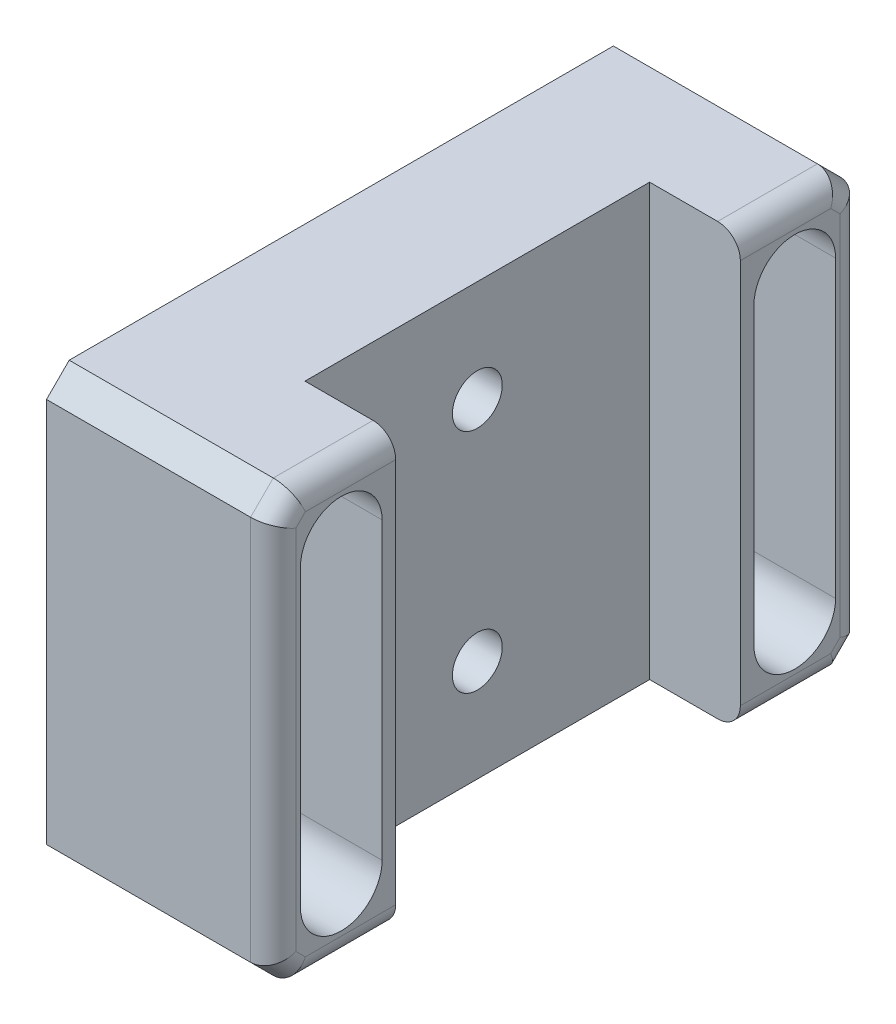
SolidWorks part; units mm, degrees
ref_plane "Спереди" through (0, 0, 0) normal (0, 0, 1) x (1, 0, 0)
ref_plane "Сверху" through (0, 0, 0) normal (0, 1, 0) x (1, 0, 0)
ref_plane "Справа" through (0, 0, 0) normal (1, 0, 0) x (0, 0, -1)
sketch "Эскиз1" plane through (0, 0, 0) normal (1, 0, 0) x (0, 0, -1)
  line L0 (-10, 6.5) -> (-10, -6.5) construction
  line L1 (-13, 9.5) -> (13, 9.5)
  line L2 (-13, 9.5) -> (-13, -9.5)
  line L3 (-13, -9.5) -> (13, -9.5)
  line L4 (13, 9.5) -> (13, -9.5)
  line L5 (-13, 9.5) -> (13, -9.5) construction
  line L6 (-13, -9.5) -> (13, 9.5) construction
  line L7 (-8.9, 6.5) -> (-8.9, -6.5)
  line L8 (-11.1, 6.5) -> (-11.1, -6.5)
  line L9 (0, 9.5) -> (0, -9.5) construction
  line L10 (10, 6.5) -> (10, -6.5) construction
  line L11 (8.9, 6.5) -> (8.9, -6.5)
  line L12 (11.1, 6.5) -> (11.1, -6.5)
  arc A0 (-8.9, 6.5) -> (-11.1, 6.5) centre (-10, 6.5) ccw
  arc A1 (-11.1, -6.5) -> (-8.9, -6.5) centre (-10, -6.5) ccw
  arc A2 (8.9, 6.5) -> (11.1, 6.5) centre (10, 6.5) cw
  arc A3 (11.1, -6.5) -> (8.9, -6.5) centre (10, -6.5) cw
  point P0 (0, 0)
  point P8 (-10, 0)
  point P17 (10, 0)
  dimension "D1" = 26
  dimension "D2" = 2.2
  dimension "D3" = 20
  dimension "D5" = 3
  dimension "D4" = 19
extrude "Бобышка-Вытянуть1" add sketch "Эскиз1" along normal blind 10
sketch "Эскиз2" plane through (10, 0, 0) normal (1, 0, 0) x (0, 0, -1)
  line L0 (-13, -9.5) -> (13, -9.5) construction
  line L1 (7.6, 9.5) -> (-7.6, 9.5)
  line L2 (7.6, 9.5) -> (7.6, -9.5)
  line L3 (7.6, -9.5) -> (-7.6, -9.5)
  line L4 (-7.6, 9.5) -> (-7.6, -9.5)
  line L5 (7.6, 9.5) -> (-7.6, -9.5) construction
  line L6 (7.6, -9.5) -> (-7.6, 9.5) construction
  point P0 (0, 0)
  dimension "D1" = 15.2
extrude "Вырез-Вытянуть1" cut sketch "Эскиз2" against normal blind 4
sketch "Эскиз3" plane through (10, 0, 0) normal (1, 0, 0) x (0, 0, -1)
  line L0 (-10, -6.5) -> (-10, 6.5) construction
  line L1 (-11.8, -6.5) -> (-11.8, 6.5)
  line L2 (-8.2, -6.5) -> (-8.2, 6.5)
  line L3 (0, 9.5) -> (0, -9.5) construction
  line L4 (7.6, 9.5) -> (-7.6, 9.5) construction
  line L5 (-7.6, -9.5) -> (7.6, -9.5) construction
  line L6 (10, -6.5) -> (10, 6.5) construction
  line L7 (11.8, -6.5) -> (11.8, 6.5)
  line L8 (8.2, -6.5) -> (8.2, 6.5)
  arc A0 (-11.8, -6.5) -> (-8.2, -6.5) centre (-10, -6.5) ccw
  arc A1 (-8.2, 6.5) -> (-11.8, 6.5) centre (-10, 6.5) ccw
  arc A2 (-11.1, -6.5) -> (-8.9, -6.5) centre (-10, -6.5) ccw construction
  arc A3 (-8.9, 6.5) -> (-11.1, 6.5) centre (-10, 6.5) ccw construction
  arc A4 (11.8, -6.5) -> (8.2, -6.5) centre (10, -6.5) cw
  arc A5 (8.2, 6.5) -> (11.8, 6.5) centre (10, 6.5) cw
  point P2 (-10, 0)
  point P23 (10, 0)
  dimension "D1" = 3.6
extrude "Вырез-Вытянуть2" cut sketch "Эскиз3" against normal blind 4
chamfer "Фаска1" distance 1 angle 45 4 edges at (5, 9.5, -13) (5, -9.5, -13) (5, -9.5, 13) (5, 9.5, 13)
fillet "Скругление1" radius 1 10 edges at (10, 9, 12.5) (10, -9, 12.5) (10, -9, -12.5) (10, -9.5, -9.8) (10, 0, -13) (10, 9, -12.5) (10, 9.5, -9.8) (10, -9.5, 9.8) (10, 9.5, 9.8) (10, 0, 13)
sketch "Эскиз4" plane through (6, 0, 0) normal (1, 0, 0) x (0, 0, -1)
  line L0 (0, 9.5) -> (0, -9.5) construction
  line L1 (7.6, 9.5) -> (-7.6, 9.5) construction
  line L2 (-7.6, -9.5) -> (7.6, -9.5) construction
  line L3 (-7.6, 0) -> (7.6, 0) construction
  line L4 (-7.6, 9.5) -> (-7.6, -9.5) construction
  line L5 (7.6, -9.5) -> (7.6, 9.5) construction
  circle A0 centre (0, 5) radius 1.1
  circle A1 centre (0, -5) radius 1.1
  dimension "D1" = 2.2
  dimension "D2" = 10
extrude "Вырез-Вытянуть3" cut sketch "Эскиз4" against normal through all
sketch "Эскиз5" plane through (0, 0, 0) normal (-1, 0, 0) x (0, 0, 1)
  line L1 (1.1258, 3.05) -> (2.2517, 5)
  line L2 (2.2517, 5) -> (1.1258, 6.95)
  line L3 (1.1258, 6.95) -> (-1.1258, 6.95)
  line L4 (-1.1258, 6.95) -> (-2.2517, 5)
  line L5 (-2.2517, 5) -> (-1.1258, 3.05)
  line L6 (-1.1258, 3.05) -> (1.1258, 3.05)
  line L7 (1.1258, -6.95) -> (2.2517, -5)
  line L8 (2.2517, -5) -> (1.1258, -3.05)
  line L9 (1.1258, -3.05) -> (-1.1258, -3.05)
  line L10 (-1.1258, -3.05) -> (-2.2517, -5)
  line L11 (-2.2517, -5) -> (-1.1258, -6.95)
  line L12 (-1.1258, -6.95) -> (1.1258, -6.95)
  circle A0 centre (0, 5) radius 1.95 construction
  circle A1 centre (0, -5) radius 1.95 construction
  dimension "D1" = 3.9
  dimension "D2" = 3.9
extrude "Вырез-Вытянуть4" cut sketch "Эскиз5" against normal blind 3
equation "\"motor_diameter\"= 30"
equation "\"mm_diameter\"= IIF ( \"motor_diameter\" < 34 , 41 , \"motor_diameter\" + 8 )"
equation "\"upper_shafts_diameter\"= 5"
equation "\"upper_shats_length\"= 180"
equation "\"upper_bearing_d1\"= 10"
equation "\"upper_bearing_d2\"= 5"
equation "\"upper_bearing_h\"= 15"
equation "\"lower_shafts_diameter\"= 5"
equation "\"lower_shafts_length\"= 180"
equation "\"lower_bearing_d1\"= 10"
equation "\"lower_bearing_d2\"= 5"
equation "\"lower_bearing_h\"= 15"
equation "\"print_offset\"= 0.2"
equation "\"bh_screws_d\"= 2"
equation "\"bh_screws_h\"= 20"
equation "\"bh_screws_hh_d\"= 3.4"
equation "\"bh_screws_hh_h\"= 2"
equation "\"bh_nut_d\"= 3.8"
equation "\"bh_nut_h\"= 2"
equation "\"motor_screws_d\"= 3"
equation "\"motor_screws_h\"= 16"
equation "\"motor_screws_hh_d\"= 5.5"
equation "\"motor_screws_hh_h\"= 3"
equation "\"plate_hole_distance\"= 25.4"
equation "\"plate_screws_d\"= 6.5"
equation "\"shafts_diameter\"= IIF ( \"mm_diameter\" < 42 , 42 + 8 , \"mm_diameter\" + 8 )"
equation "\"central_hole_diameter\"= 8"
equation "\"bh_thikness\"= 4"
equation "\"ends_screws_d\"= 4"
equation "\"ends_screws_h\"= 16"
equation "\"ends_screws_hh_d\"= 6.7"
equation "\"ends_screws_hh_h\"= 4.1"
equation "\"ends_nut_d\"= 6.8"
equation "\"ends_nut_h\"= 3"
equation "\"system_radius\" = ( \"shafts_diameter\" + 12 + \"bh_thikness\" / 2 ) / 2"
equation "\"encoder_distance\"= \"system_radius\" + 4"
equation "\"tape_position\"= \"encoder_distance\" - 2 + 3.9 + 1.7 / 2"
equation "\"D2@Эскиз1\"=\"bh_screws_d\"+\"print_offset\""
equation "\"D1@Бобышка-Вытянуть1\"=6"
equation "\"D4@Эскиз1\"=\"upper_bearing_h\" + 6 + 3 - 8 + 3"
equation "\"D1@Эскиз2\"=\"print_offset\"+15"
equation "\"D1@Эскиз3\"=\"bh_screws_hh_d\"+\"print_offset\""
equation "\"D1@Вырез-Вытянуть2\"=\"bh_screws_hh_h\"+2"
equation "\"D1@Эскиз4\"=\"bh_screws_d\"+\"print_offset\""
equation "\"D1@Эскиз5\"=\"bh_nut_d\"+\"print_offset\"/2"
equation "\"D2@Эскиз5\"=\"D1@Эскиз5\""
equation "\"D1@Вырез-Вытянуть4\"=\"bh_nut_h\"+1"
equation "\"ft_sensor_d1\" = 9.8"
equation "\"ft_sensor_d2\"= 24.9"
equation "\"ft_sensor_h\"= 7"
equation "\"carbon_pipe_d\"= 14"
